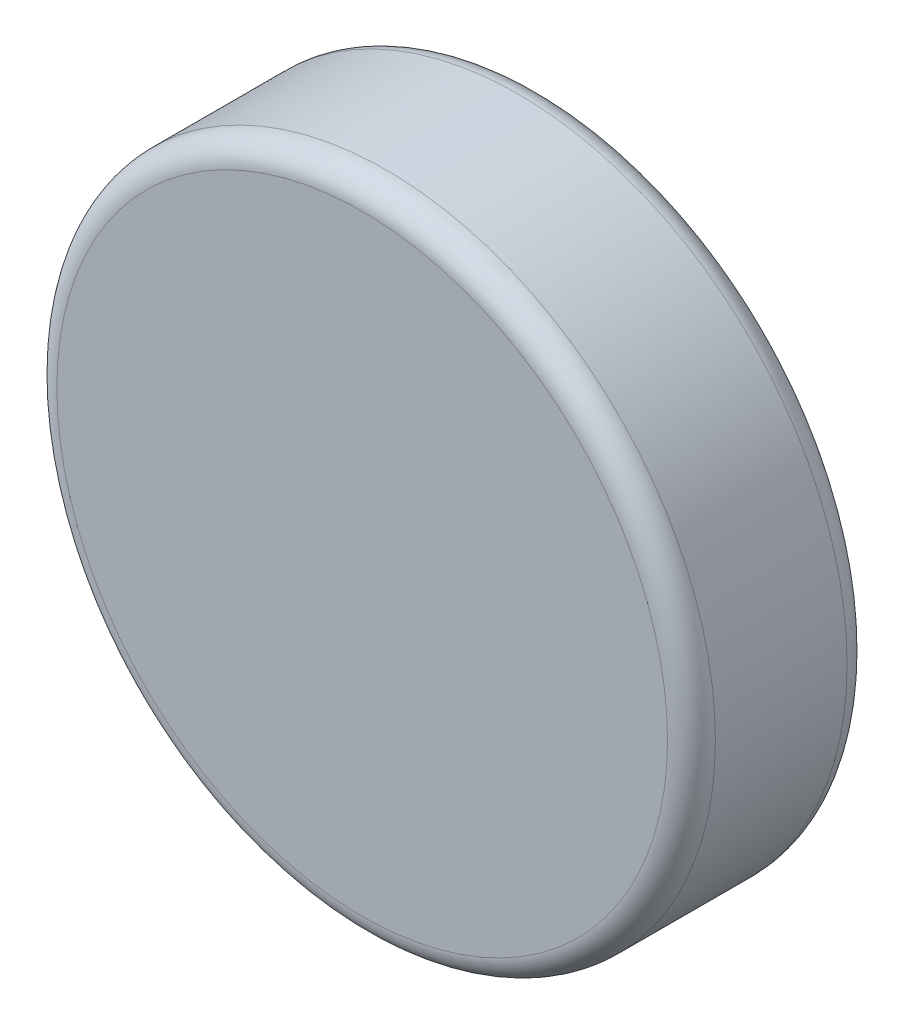
SolidWorks part; units mm, degrees
ref_plane "Přední rovina" through (0, 0, 0) normal (0, 0, 1) x (1, 0, 0)
ref_plane "Vrchní rovina" through (0, 0, 0) normal (0, 1, 0) x (1, 0, 0)
ref_plane "Pravá rovina" through (0, 0, 0) normal (1, 0, 0) x (0, 0, -1)
sketch "Skica1" plane through (0, 0, 0) normal (0, 0, 1) x (1, 0, 0)
  circle A0 centre (0, 0) radius 27.5
  dimension "D1" = 55
extrude "Přidat vysunutím1" add sketch "Skica1" along normal blind 15
fillet "Zaoblit1" radius 2 2 edges at (27.5, 0, 0) (27.5, 0, 15)
